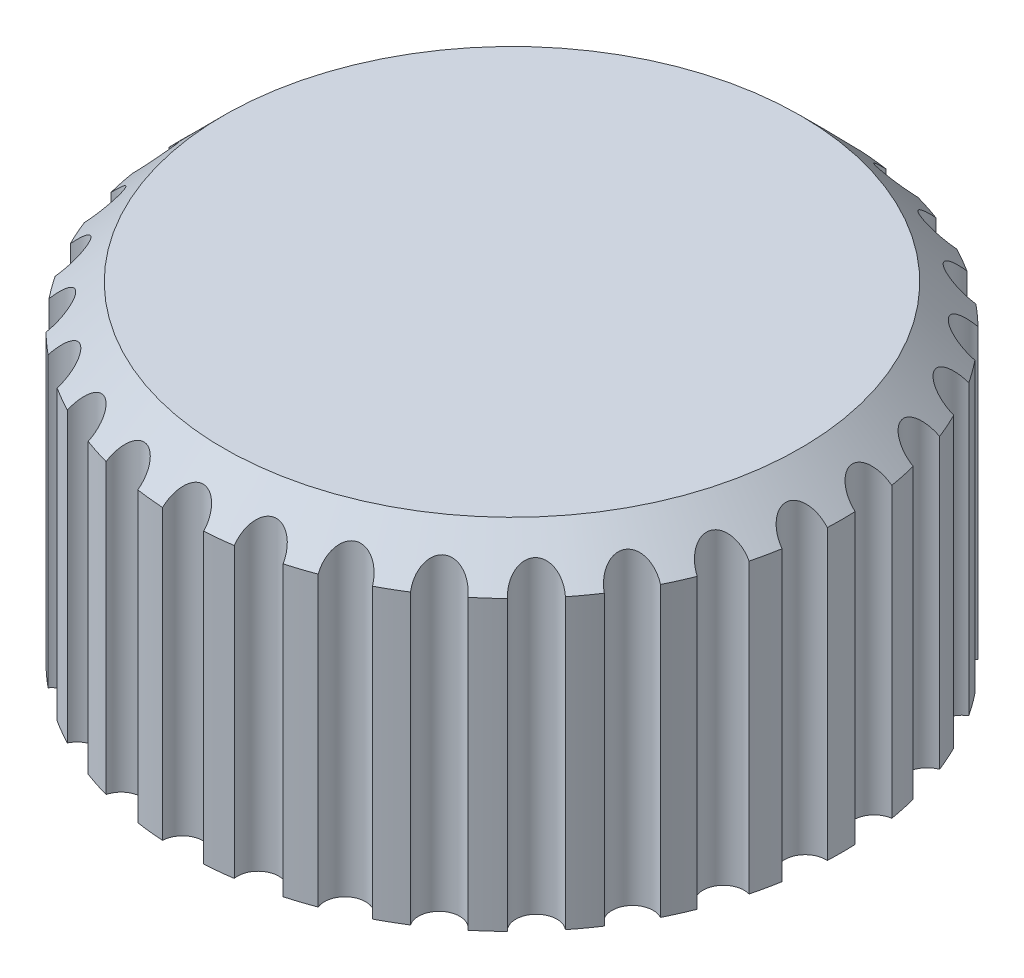
SolidWorks part; units mm, degrees
ref_plane "Front Plane" through (0, 0, 0) normal (0, 0, 1) x (1, 0, 0)
ref_plane "Top Plane" through (0, 0, 0) normal (0, 1, 0) x (1, 0, 0)
ref_plane "Right Plane" through (0, 0, 0) normal (1, 0, 0) x (0, 0, -1)
sketch "Sketch1" plane through (0, 0, 0) normal (0, 1, 0) x (1, 0, 0)
  line L0 (0, 0) -> (0, 24.0976) construction
  circle A0 centre (0, 0) radius 16
  circle A1 centre (0, 16) radius 1
  circle A2 centre (3.3266, 15.6504) radius 1
  circle A3 centre (6.5078, 14.6167) radius 1
  circle A4 centre (9.4046, 12.9443) radius 1
  circle A5 centre (11.8903, 10.7061) radius 1
  circle A6 centre (13.8564, 8) radius 1
  circle A7 centre (15.2169, 4.9443) radius 1
  circle A8 centre (15.9124, 1.6725) radius 1
  circle A9 centre (15.9124, -1.6725) radius 1
  circle A10 centre (15.2169, -4.9443) radius 1
  circle A11 centre (13.8564, -8) radius 1
  circle A12 centre (11.8903, -10.7061) radius 1
  circle A13 centre (9.4046, -12.9443) radius 1
  circle A14 centre (6.5078, -14.6167) radius 1
  circle A15 centre (3.3266, -15.6504) radius 1
  circle A16 centre (0, -16) radius 1
  circle A17 centre (-3.3266, -15.6504) radius 1
  circle A18 centre (-6.5078, -14.6167) radius 1
  circle A19 centre (-9.4046, -12.9443) radius 1
  circle A20 centre (-11.8903, -10.7061) radius 1
  circle A21 centre (-13.8564, -8) radius 1
  circle A22 centre (-15.2169, -4.9443) radius 1
  circle A23 centre (-15.9124, -1.6725) radius 1
  circle A24 centre (-15.9124, 1.6725) radius 1
  circle A25 centre (-15.2169, 4.9443) radius 1
  circle A26 centre (-13.8564, 8) radius 1
  circle A27 centre (-11.8903, 10.7061) radius 1
  circle A28 centre (-9.4046, 12.9443) radius 1
  circle A29 centre (-6.5078, 14.6167) radius 1
  circle A30 centre (-3.3266, 15.6504) radius 1
  point P66 (0, 0)
  dimension "D1" = 32
  dimension "D2" = 2
  dimension "D4" = 30
extrude "Boss-Extrude2" add sketch "Sketch1" along normal blind 16 contours A30 A0 A29 A28 A27 A26 A25 A24 A23 A22 A21 A20 A19 A18 A17 A16 A15 A14 A13 A12 A11 A10 A9 A8 A7 A6 A5
sketch "Sketch2" plane through (0, 0, 0) normal (0, 0, 1) x (1, 0, 0)
  line L0 (-16, 16) -> (-16, 14)
  line L1 (-16, 16) -> (-16, 0) construction
  line L2 (-16, 14) -> (-14, 16)
  line L3 (-14.3291, 16) -> (-14.8783, 16) construction
  line L4 (-14, 16) -> (-16, 16)
  line L5 (0, 0) -> (0, 24.2768) construction
  dimension "D1" = 2
  dimension "D2" = 2
revolve "Cut-Revolve1" cut sketch "Sketch2" angle 360 about L5
sketch "Sketch3" plane through (0, 0, 0) normal (0, -1, 0) x (1, 0, 0)
  circle A0 centre (0, 0) radius 12.5
  arc A1 (-0.9995, 15.9688) -> (-2.3424, 15.8276) centre (0, 0) ccw construction
  dimension "D1" = 3.5
extrude "Cut-Extrude1" cut sketch "Sketch3" against normal offset from surface (12 mm away) 4 up to face at (0, 16, -14)
sketch "Sketch4" plane through (0, 12, 0) normal (0, -1, 0) x (1, 0, 0)
  line L0 (-4.9682, 3) -> (4.6008, 3) construction
  line L1 (2.5981, -1.5) -> (-2.5981, -1.5)
  arc A0 (2.5981, -1.5) -> (-2.5981, -1.5) centre (0, 0) ccw
  circle A1 centre (0, 0) radius 7
  dimension "D1" = 6
  dimension "D3" = 4
  dimension "D2" = 4.5
extrude "Boss-Extrude3" add sketch "Sketch4" along normal blind 8 from surface at 0 starting at face at (0, 12, 12.5)
fillet "Fillet2" radius 1 4 edges at (0, 4, 7) (0, 12, 7) (0, 12, 12.5) (0, 0, -12.5)
